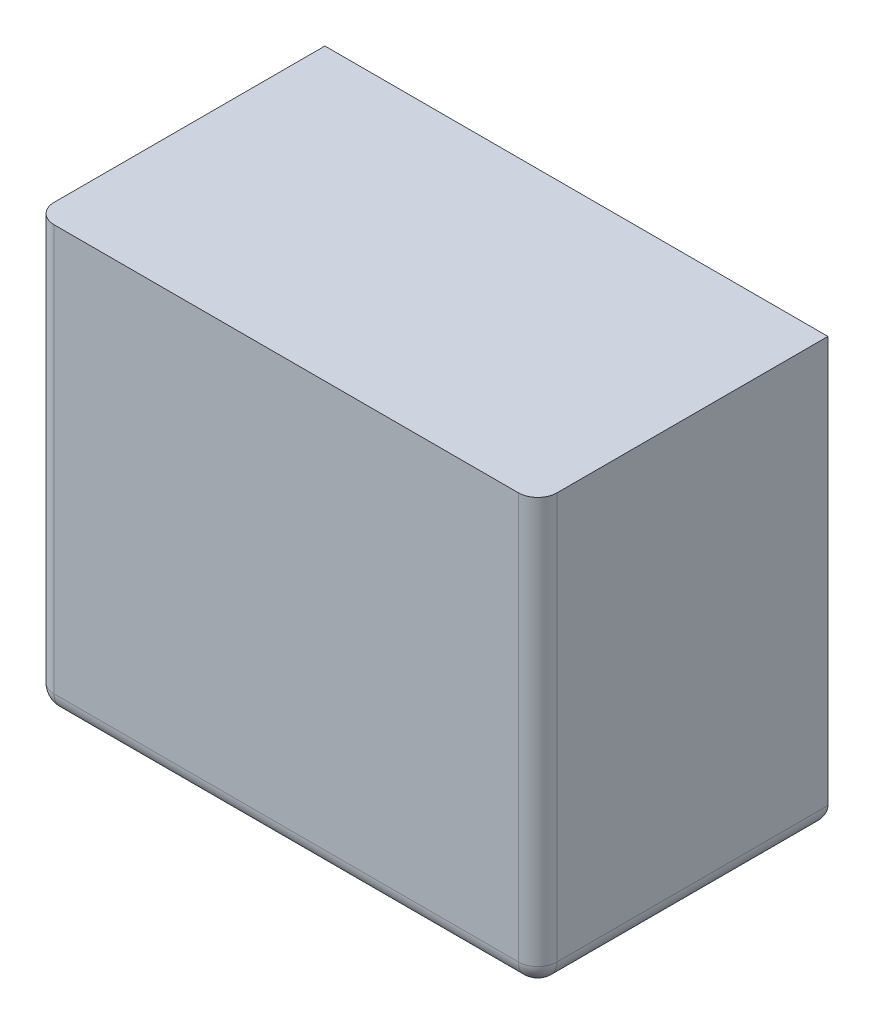
SolidWorks part; units mm, degrees
ref_plane "Front Plane" through (0, 0, 0) normal (0, 0, 1) x (1, 0, 0)
ref_plane "Top Plane" through (0, 0, 0) normal (0, 1, 0) x (1, 0, 0)
ref_plane "Right Plane" through (0, 0, 0) normal (1, 0, 0) x (0, 0, -1)
sketch "Sketch2" plane through (0, 0, 0) normal (0, 0, 1) x (1, 0, 0)
  line L0 (0, 0) -> (0, -220)
  line L1 (0, -220) -> (260, -220)
  line L2 (260, -220) -> (260, 0)
  line L3 (260, 0) -> (0, 0)
  dimension "D1" = 220
  dimension "D2" = 260
extrude "Boss-Extrude1" add sketch "Sketch2" along normal blind 150
fillet "Fillet1" radius 10 6 edges at (130, -220, 0) (260, -110, 150) (260, -220, 75) (130, -220, 150) (0, -220, 75) (0, -110, 150)
